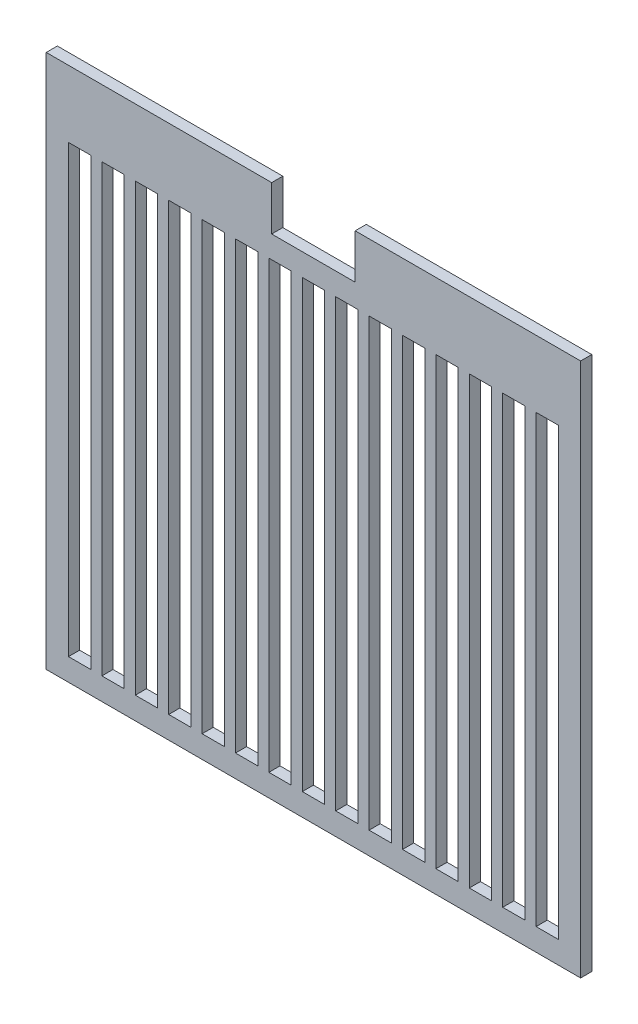
SolidWorks part; units mm, degrees
ref_plane "Front Plane" through (0, 0, 0) normal (0, 0, 1) x (1, 0, 0)
ref_plane "Top Plane" through (0, 0, 0) normal (0, 1, 0) x (1, 0, 0)
ref_plane "Right Plane" through (0, 0, 0) normal (1, 0, 0) x (0, 0, -1)
sketch "Sketch1" plane through (0, 0, 0) normal (0, 0, 1) x (1, 0, 0)
  line L1 (0, 0) -> (96, 0)
  line L2 (0, 0) -> (0, 96)
  line L3 (0, 96) -> (96, 96)
  line L4 (96, 0) -> (96, 96)
  dimension "D1" = 96
  dimension "D2" = 96
extrude "Boss-Extrude2" add sketch "Sketch1" along normal blind 2 contours L2 L1 L4 L3
sketch "Finger Opening Hole" plane through (0, 0, 2) normal (0, 0, 1) x (1, 0, 0)
  line L0 (48, 96) -> (48, 88) construction
  line L1 (0, 96) -> (96, 96) construction
  line L2 (48, 88) -> (55.5, 88) construction
  line L3 (48, 88) -> (40.5, 88) construction
  line L5 (40.5, 88) -> (55.5, 88)
  line L6 (40.5, 88) -> (40.5, 96)
  line L7 (40.5, 96) -> (55.5, 96)
  line L8 (55.5, 88) -> (55.5, 96)
  dimension "D1" = 8
  dimension "D2" = 7.5
  dimension "D3" = 7.5
sketch "Airflow" plane through (0, 0, 2) normal (0, 0, 1) x (1, 0, 0)
  line L0 (0, 48) -> (96, 48) construction
  line L1 (0, 0) -> (0, 96) construction
  line L2 (96, 0) -> (96, 96) construction
  line L3 (48, 0) -> (48, 96) construction
  line L4 (0, 0) -> (96, 0) construction
  line L5 (0, 0) -> (4, 0) construction
  line L6 (0, 0) -> (0, 4) construction
  line L7 (0, 4) -> (4, 4) construction
  line L8 (4, 4) -> (4, 0) construction
  line L9 (96, 0) -> (92, 0) construction
  line L10 (96, 0) -> (96, 4) construction
  line L11 (92, 0) -> (92, 4) construction
  line L12 (92, 4) -> (96, 4) construction
  line L13 (4, 4) -> (92, 4) construction
  line L14 (4, 4) -> (4, 96) construction
  line L15 (0, 96) -> (96, 96) construction
  line L16 (0, 96) -> (0, 84) construction
  line L17 (0, 84) -> (96, 84) construction
  line L18 (92, 4) -> (92, 96) construction
  line L19 (10, 4) -> (10, 84)
  line L20 (4, 4) -> (8, 4)
  line L21 (4, 4) -> (4, 84)
  line L22 (4, 84) -> (8, 84)
  line L23 (8, 4) -> (8, 84)
  line L24 (10, 4) -> (14, 4)
  line L25 (14, 4) -> (14, 84)
  line L26 (10, 84) -> (14, 84)
  line L27 (16, 4) -> (16, 84)
  line L28 (16, 4) -> (20, 4)
  line L29 (20, 4) -> (20, 84)
  line L30 (16, 84) -> (20, 84)
  line L31 (22, 4) -> (22, 84)
  line L32 (22, 4) -> (26, 4)
  line L33 (26, 4) -> (26, 84)
  line L34 (22, 84) -> (26, 84)
  line L35 (28, 4) -> (28, 84)
  line L36 (28, 4) -> (32, 4)
  line L37 (32, 4) -> (32, 84)
  line L38 (28, 84) -> (32, 84)
  line L39 (34, 4) -> (34, 84)
  line L40 (34, 4) -> (38, 4)
  line L41 (38, 4) -> (38, 84)
  line L42 (34, 84) -> (38, 84)
  line L43 (40, 4) -> (40, 84)
  line L44 (40, 4) -> (44, 4)
  line L45 (44, 4) -> (44, 84)
  line L46 (40, 84) -> (44, 84)
  line L47 (46, 4) -> (46, 84)
  line L48 (46, 4) -> (50, 4)
  line L49 (50, 4) -> (50, 84)
  line L50 (46, 84) -> (50, 84)
  line L51 (52, 4) -> (52, 84)
  line L52 (52, 4) -> (56, 4)
  line L53 (56, 4) -> (56, 84)
  line L54 (52, 84) -> (56, 84)
  line L55 (58, 4) -> (58, 84)
  line L56 (58, 4) -> (62, 4)
  line L57 (62, 4) -> (62, 84)
  line L58 (58, 84) -> (62, 84)
  line L59 (64, 4) -> (64, 84)
  line L60 (64, 4) -> (68, 4)
  line L61 (68, 4) -> (68, 84)
  line L62 (64, 84) -> (68, 84)
  line L63 (70, 4) -> (70, 84)
  line L64 (70, 4) -> (74, 4)
  line L65 (74, 4) -> (74, 84)
  line L66 (70, 84) -> (74, 84)
  line L67 (76, 4) -> (76, 84)
  line L68 (76, 4) -> (80, 4)
  line L69 (80, 4) -> (80, 84)
  line L70 (76, 84) -> (80, 84)
  line L71 (82, 4) -> (82, 84)
  line L72 (82, 4) -> (86, 4)
  line L73 (86, 4) -> (86, 84)
  line L74 (82, 84) -> (86, 84)
  line L75 (88, 4) -> (88, 84)
  line L76 (88, 4) -> (92, 4)
  line L77 (92, 4) -> (92, 84)
  line L78 (88, 84) -> (92, 84)
  dimension "D1" = 4
  dimension "D2" = 4
  dimension "D3" = 4
  dimension "D4" = 12
  dimension "D5" = 4
  dimension "D6" = 15
extrude "Opening Hole" cut sketch "Finger Opening Hole" against normal blind 2
extrude "Air Flow" cut sketch "Airflow" against normal blind 2
equation "\"L\"= 100mm"
equation "\"T\"= 1mm"
equation "\"D1@Sketch1\"=(24/25)*\"L\""
equation "\"D2@Sketch1\"=(24/25)*\"L\""
equation "\"D1@Finger Opening Hole\" = 8 * \"T\""
equation "\"D2@Finger Opening Hole\" = 7.5 * \"T\""
equation "\"D3@Finger Opening Hole\" = 7.5 * \"T\""
equation "\"D1@Airflow\" = 4 * \"T\""
equation "\"D2@Airflow\" = 4 * \"T\""
equation "\"D3@Airflow\" = 4 * \"T\""
equation "\"D4@Airflow\" = 12 * \"T\""
equation "\"D5@Airflow\" = 4 * \"T\""
